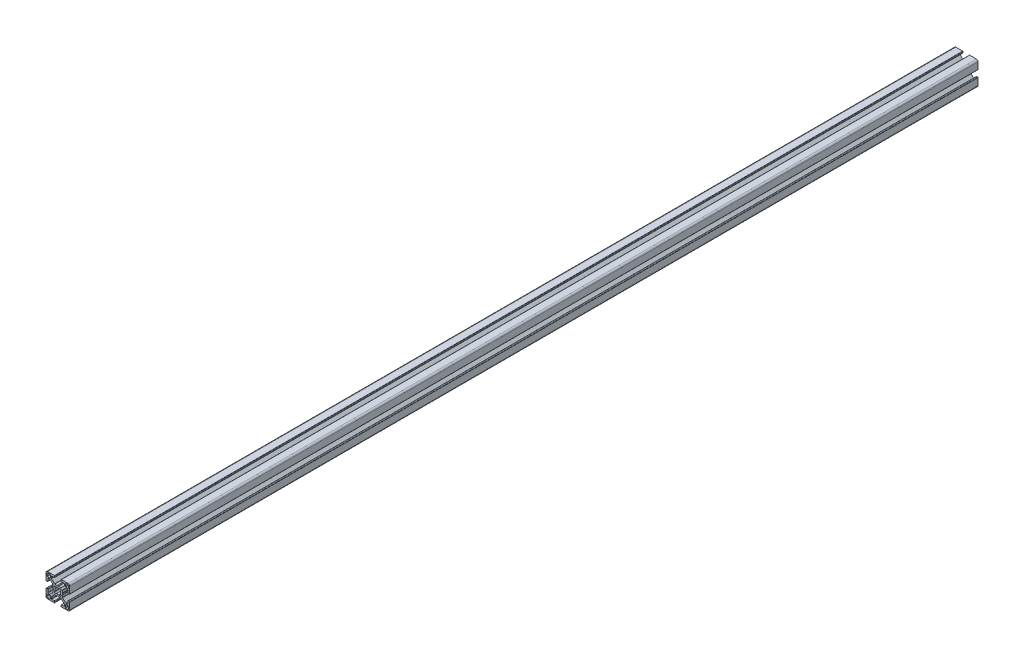
SolidWorks part; units mm, degrees
material "6105-T5 Aluminum"
ref_plane "Front Plane" through (0, 0, 0) normal (0, 0, 1) x (1, 0, 0)
ref_plane "Top Plane" through (0, 0, 0) normal (0, 1, 0) x (1, 0, 0)
ref_plane "Right Plane" through (0, 0, 0) normal (1, 0, 0) x (0, 0, -1)
sketch "Sketch1" plane through (0, 0, 0) normal (0, 0, 1) x (1, 0, 0)
  line L0 (9.5, -13.3189) -> (9.5, -9.88)
  line L1 (9.88, -9.5) -> (13.3189, -9.5)
  line L2 (13.6999, -9.881) -> (13.6999, -12.6999)
  line L3 (12.6999, -13.6999) -> (9.881, -13.6999)
  line L4 (-13.3189, -9.5) -> (-9.88, -9.5)
  line L5 (-9.5, -9.88) -> (-9.5, -13.3189)
  line L6 (-9.881, -13.6999) -> (-12.6999, -13.6999)
  line L7 (-13.6999, -12.6999) -> (-13.6999, -9.881)
  line L8 (-1.4942, -3.1981) -> (-2.4733, -3.9799)
  line L9 (-3.9799, -2.4733) -> (-3.1981, -1.4942)
  line L10 (-3.1981, 1.4942) -> (-3.9799, 2.4733)
  line L11 (-2.4733, 3.9799) -> (-1.4942, 3.1981)
  line L12 (1.4942, 3.1981) -> (2.4733, 3.9799)
  line L13 (3.9799, 2.4733) -> (3.1981, 1.4942)
  line L14 (3.1981, -1.4942) -> (3.9799, -2.4733)
  line L15 (2.4733, -3.9799) -> (1.4942, -3.1981)
  line L16 (-9.5, 13.3189) -> (-9.5, 9.88)
  line L17 (-9.88, 9.5) -> (-13.3189, 9.5)
  line L18 (-13.6999, 9.881) -> (-13.6999, 12.6999)
  line L19 (-12.6999, 13.6999) -> (-9.881, 13.6999)
  line L20 (9.881, 13.6999) -> (12.6999, 13.6999)
  line L21 (13.6999, 12.6999) -> (13.6999, 9.881)
  line L22 (13.3189, 9.5) -> (9.88, 9.5)
  line L23 (9.5, 9.88) -> (9.5, 13.3189)
  line L24 (12.7425, -4.5) -> (12.7425, -7.7325)
  line L25 (12.2428, -8.25) -> (10.2602, -8.25)
  line L26 (9.9066, -8.1035) -> (5.9811, -4.178)
  line L27 (5.8347, -3.8245) -> (5.8347, -1.0125)
  line L28 (5.8347, -1.0125) -> (5.3247, -0.0625)
  line L29 (5.3247, -0.0625) -> (5.8347, 0.8875)
  line L30 (5.8347, 0.8875) -> (5.8347, 3.8245)
  line L31 (5.9811, 4.178) -> (9.9066, 8.1035)
  line L32 (10.2602, 8.25) -> (12.2428, 8.25)
  line L33 (12.7425, 7.7325) -> (12.7425, 4.5)
  line L34 (13.2425, 4) -> (14.4999, 4)
  line L35 (14.9999, 4.5) -> (14.9999, 12.9999)
  line L36 (12.9999, 14.9999) -> (4.5, 14.9999)
  line L37 (4, 14.4999) -> (4, 13.2425)
  line L38 (4.5, 12.7425) -> (7.7325, 12.7425)
  line L39 (8.25, 12.2428) -> (8.25, 10.2602)
  line L40 (8.1035, 9.9066) -> (4.178, 5.9811)
  line L41 (3.8245, 5.8347) -> (0.95, 5.8347)
  line L42 (0.95, 5.8347) -> (0, 5.3247)
  line L43 (0, 5.3247) -> (-0.95, 5.8347)
  line L44 (-0.95, 5.8347) -> (-3.8245, 5.8347)
  line L45 (-4.178, 5.9811) -> (-8.1035, 9.9066)
  line L46 (-8.25, 10.2602) -> (-8.25, 12.2428)
  line L47 (-7.7325, 12.7425) -> (-4.5, 12.7425)
  line L48 (-4, 13.2425) -> (-4, 14.4999)
  line L49 (-4.5, 14.9999) -> (-12.9999, 14.9999)
  line L50 (-14.9999, 12.9999) -> (-14.9999, 4.5)
  line L51 (-14.4999, 4) -> (-13.2425, 4)
  line L52 (-12.7425, 4.5) -> (-12.7425, 7.7325)
  line L53 (-12.2428, 8.25) -> (-10.2602, 8.25)
  line L54 (-9.9066, 8.1035) -> (-5.9811, 4.178)
  line L55 (-5.8347, 3.8245) -> (-5.8347, 0.8875)
  line L56 (-5.8347, 0.8875) -> (-5.3247, -0.0625)
  line L57 (-5.3247, -0.0625) -> (-5.8347, -1.0125)
  line L58 (-5.8347, -1.0125) -> (-5.8347, -3.8245)
  line L59 (-5.9811, -4.178) -> (-9.9066, -8.1035)
  line L60 (-10.2602, -8.25) -> (-12.2428, -8.25)
  line L61 (-12.7425, -7.7325) -> (-12.7425, -4.5)
  line L62 (-13.2425, -4) -> (-14.4999, -4)
  line L63 (-14.9999, -4.5) -> (-14.9999, -12.9999)
  line L64 (-12.9999, -14.9999) -> (-4.5, -14.9999)
  line L65 (-4, -14.4999) -> (-4, -13.2425)
  line L66 (-4.5, -12.7425) -> (-7.7325, -12.7425)
  line L67 (-8.25, -12.2428) -> (-8.25, -10.2602)
  line L68 (-8.1035, -9.9066) -> (-4.178, -5.9811)
  line L69 (-3.8245, -5.8347) -> (-0.95, -5.8347)
  line L70 (-0.95, -5.8347) -> (0, -5.3247)
  line L71 (0, -5.3247) -> (0.95, -5.8347)
  line L72 (0.95, -5.8347) -> (3.8245, -5.8347)
  line L73 (4.178, -5.9811) -> (8.1035, -9.9066)
  line L74 (8.25, -10.2602) -> (8.25, -12.2428)
  line L75 (7.7325, -12.7425) -> (4.5, -12.7425)
  line L76 (4, -13.2425) -> (4, -14.4999)
  line L77 (4.5, -14.9999) -> (12.9999, -14.9999)
  line L78 (14.9999, -12.9999) -> (14.9999, -4.5)
  line L79 (14.4999, -4) -> (13.2425, -4)
  arc A0 (9.5, -13.3189) -> (9.881, -13.6999) centre (9.881, -13.3189) ccw
  arc A1 (9.88, -9.5) -> (9.5, -9.88) centre (9.88, -9.88) ccw
  arc A2 (13.6999, -9.881) -> (13.3189, -9.5) centre (13.3189, -9.881) ccw
  arc A3 (12.6999, -13.6999) -> (13.6999, -12.6999) centre (12.6999, -12.6999) ccw
  arc A4 (-13.3189, -9.5) -> (-13.6999, -9.881) centre (-13.3189, -9.881) ccw
  arc A5 (-9.5, -9.88) -> (-9.88, -9.5) centre (-9.88, -9.88) ccw
  arc A6 (-9.881, -13.6999) -> (-9.5, -13.3189) centre (-9.881, -13.3189) ccw
  arc A7 (-13.6999, -12.6999) -> (-12.6999, -13.6999) centre (-12.6999, -12.6999) ccw
  arc A8 (-1.4942, -3.1981) -> (1.4942, -3.1981) centre (0, 0) ccw
  arc A9 (-3.9799, -2.4733) -> (-2.4733, -3.9799) centre (-3.1422, -3.1422) ccw
  arc A10 (-3.1981, 1.4942) -> (-3.1981, -1.4942) centre (0, 0) ccw
  arc A11 (-2.4733, 3.9799) -> (-3.9799, 2.4733) centre (-3.1422, 3.1422) ccw
  arc A12 (1.4942, 3.1981) -> (-1.4942, 3.1981) centre (0, 0) ccw
  arc A13 (3.9799, 2.4733) -> (2.4733, 3.9799) centre (3.1422, 3.1422) ccw
  arc A14 (3.1981, -1.4942) -> (3.1981, 1.4942) centre (0, 0) ccw
  arc A15 (2.4733, -3.9799) -> (3.9799, -2.4733) centre (3.1422, -3.1422) ccw
  arc A16 (-9.5, 13.3189) -> (-9.881, 13.6999) centre (-9.881, 13.3189) ccw
  arc A17 (-9.88, 9.5) -> (-9.5, 9.88) centre (-9.88, 9.88) ccw
  arc A18 (-13.6999, 9.881) -> (-13.3189, 9.5) centre (-13.3189, 9.881) ccw
  arc A19 (-12.6999, 13.6999) -> (-13.6999, 12.6999) centre (-12.6999, 12.6999) ccw
  arc A20 (9.881, 13.6999) -> (9.5, 13.3189) centre (9.881, 13.3189) ccw
  arc A21 (13.6999, 12.6999) -> (12.6999, 13.6999) centre (12.6999, 12.6999) ccw
  arc A22 (13.3189, 9.5) -> (13.6999, 9.881) centre (13.3189, 9.881) ccw
  arc A23 (9.5, 9.88) -> (9.88, 9.5) centre (9.88, 9.88) ccw
  arc A24 (13.2425, -4) -> (12.7425, -4.5) centre (13.2425, -4.5) ccw
  arc A25 (12.2428, -8.25) -> (12.7425, -7.7325) centre (12.2428, -7.75) ccw
  arc A26 (9.9066, -8.1035) -> (10.2602, -8.25) centre (10.2602, -7.75) ccw
  arc A27 (5.8347, -3.8245) -> (5.9811, -4.178) centre (6.3347, -3.8245) ccw
  arc A28 (5.9811, 4.178) -> (5.8347, 3.8245) centre (6.3347, 3.8245) ccw
  arc A29 (10.2602, 8.25) -> (9.9066, 8.1035) centre (10.2602, 7.75) ccw
  arc A30 (12.7425, 7.7325) -> (12.2428, 8.25) centre (12.2428, 7.75) ccw
  arc A31 (12.7425, 4.5) -> (13.2425, 4) centre (13.2425, 4.5) ccw
  arc A32 (14.4999, 4) -> (14.9999, 4.5) centre (14.4999, 4.5) ccw
  arc A33 (14.9999, 12.9999) -> (12.9999, 14.9999) centre (12.9999, 12.9999) ccw
  arc A34 (4.5, 14.9999) -> (4, 14.4999) centre (4.5, 14.4999) ccw
  arc A35 (4, 13.2425) -> (4.5, 12.7425) centre (4.5, 13.2425) ccw
  arc A36 (8.25, 12.2428) -> (7.7325, 12.7425) centre (7.75, 12.2428) ccw
  arc A37 (8.1035, 9.9066) -> (8.25, 10.2602) centre (7.75, 10.2602) ccw
  arc A38 (3.8245, 5.8347) -> (4.178, 5.9811) centre (3.8245, 6.3347) ccw
  arc A39 (-4.178, 5.9811) -> (-3.8245, 5.8347) centre (-3.8245, 6.3347) ccw
  arc A40 (-8.25, 10.2602) -> (-8.1035, 9.9066) centre (-7.75, 10.2602) ccw
  arc A41 (-7.7325, 12.7425) -> (-8.25, 12.2428) centre (-7.75, 12.2428) ccw
  arc A42 (-4.5, 12.7425) -> (-4, 13.2425) centre (-4.5, 13.2425) ccw
  arc A43 (-4, 14.4999) -> (-4.5, 14.9999) centre (-4.5, 14.4999) ccw
  arc A44 (-12.9999, 14.9999) -> (-14.9999, 12.9999) centre (-12.9999, 12.9999) ccw
  arc A45 (-14.9999, 4.5) -> (-14.4999, 4) centre (-14.4999, 4.5) ccw
  arc A46 (-13.2425, 4) -> (-12.7425, 4.5) centre (-13.2425, 4.5) ccw
  arc A47 (-12.2428, 8.25) -> (-12.7425, 7.7325) centre (-12.2428, 7.75) ccw
  arc A48 (-9.9066, 8.1035) -> (-10.2602, 8.25) centre (-10.2602, 7.75) ccw
  arc A49 (-5.8347, 3.8245) -> (-5.9811, 4.178) centre (-6.3347, 3.8245) ccw
  arc A50 (-5.9811, -4.178) -> (-5.8347, -3.8245) centre (-6.3347, -3.8245) ccw
  arc A51 (-10.2602, -8.25) -> (-9.9066, -8.1035) centre (-10.2602, -7.75) ccw
  arc A52 (-12.7425, -7.7325) -> (-12.2428, -8.25) centre (-12.2428, -7.75) ccw
  arc A53 (-12.7425, -4.5) -> (-13.2425, -4) centre (-13.2425, -4.5) ccw
  arc A54 (-14.4999, -4) -> (-14.9999, -4.5) centre (-14.4999, -4.5) ccw
  arc A55 (-14.9999, -12.9999) -> (-12.9999, -14.9999) centre (-12.9999, -12.9999) ccw
  arc A56 (-4.5, -14.9999) -> (-4, -14.4999) centre (-4.5, -14.4999) ccw
  arc A57 (-4, -13.2425) -> (-4.5, -12.7425) centre (-4.5, -13.2425) ccw
  arc A58 (-8.25, -12.2428) -> (-7.7325, -12.7425) centre (-7.75, -12.2428) ccw
  arc A59 (-8.1035, -9.9066) -> (-8.25, -10.2602) centre (-7.75, -10.2602) ccw
  arc A60 (-3.8245, -5.8347) -> (-4.178, -5.9811) centre (-3.8245, -6.3347) ccw
  arc A61 (4.178, -5.9811) -> (3.8245, -5.8347) centre (3.8245, -6.3347) ccw
  arc A62 (8.25, -10.2602) -> (8.1035, -9.9066) centre (7.75, -10.2602) ccw
  arc A63 (7.7325, -12.7425) -> (8.25, -12.2428) centre (7.75, -12.2428) ccw
  arc A64 (4.5, -12.7425) -> (4, -13.2425) centre (4.5, -13.2425) ccw
  arc A65 (4, -14.4999) -> (4.5, -14.9999) centre (4.5, -14.4999) ccw
  arc A66 (12.9999, -14.9999) -> (14.9999, -12.9999) centre (12.9999, -12.9999) ccw
  arc A67 (14.9999, -4.5) -> (14.4999, -4) centre (14.4999, -4.5) ccw
extrude "Extrude1" add sketch "Sketch1" against normal blind 1150
sketch "Sketch3" plane through (0, 14.9999, 0) normal (0, 1, 0) x (1, 0, 0)
  line L0 (0, 1150) -> (0, 0) construction
  circle A0 centre (0, 575) radius 3.175
  dimension "D1" = 6.35
  dimension "D2" = 575
extrude "Cut-Extrude2" cut sketch "Sketch3" against normal through all
